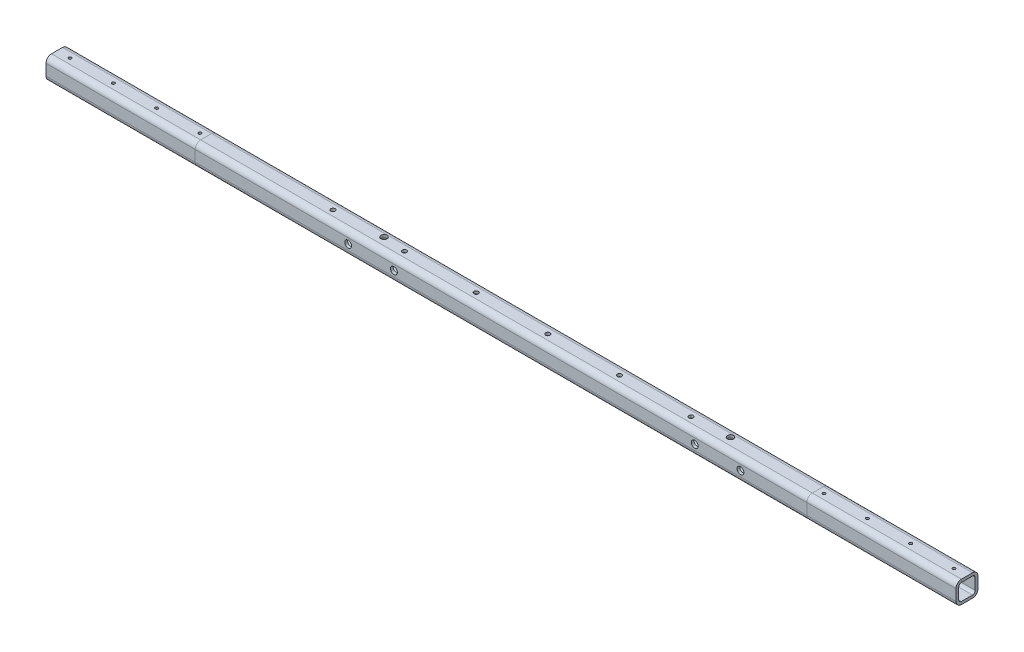
SolidWorks part; units mm, degrees
material "AISI 1015 Acero estirado en frío (SS)"
ref_plane "Alzado" through (0, 0, 0) normal (0, 0, 1) x (1, 0, 0)
ref_plane "Planta" through (0, 0, 0) normal (0, 1, 0) x (1, 0, 0)
ref_plane "Vista lateral" through (0, 0, 0) normal (1, 0, 0) x (0, 0, -1)
sketch "Croquis1" plane through (0, 0, 0) normal (0, 0, 1) x (1, 0, 0)
  line L0 (-623.6352, 0) -> (788.3648, 0)
  dimension "D1" = 1412
other "Miembro estructural1"
ref_plane "Plano1" through (-623.6352, 0, 0) normal (1, 0, 0) x (0, 1, 0)
sketch "Sketch1" plane through (-623.6352, 0, 0) normal (1, 0, 0) x (0, 1, 0)
  line L0 (-12.7, -19.05) -> (12.7, -19.05)
  line L1 (-19.05, -12.7) -> (-19.05, 12.7)
  line L2 (12.7, 19.05) -> (-12.7, 19.05)
  line L3 (19.05, 12.7) -> (19.05, -12.7)
  line L4 (-12.7, -25.4) -> (12.7, -25.4)
  line L5 (-25.4, -12.7) -> (-25.4, 12.7)
  line L6 (12.7, 25.4) -> (-12.7, 25.4)
  line L7 (25.4, 12.7) -> (25.4, -12.7)
  line L8 (0, 0) -> (19.05, 0) construction
  line L9 (0, 0) -> (0, 19.05) construction
  arc A0 (25.4, 12.7) -> (12.7, 25.4) centre (12.7, 12.7) ccw
  arc A1 (12.7, -25.4) -> (25.4, -12.7) centre (12.7, -12.7) ccw
  arc A2 (-25.4, -12.7) -> (-12.7, -25.4) centre (-12.7, -12.7) ccw
  arc A3 (-12.7, 25.4) -> (-25.4, 12.7) centre (-12.7, 12.7) ccw
  arc A4 (-12.7, 19.05) -> (-19.05, 12.7) centre (-12.7, 12.7) ccw
  arc A5 (19.05, 12.7) -> (12.7, 19.05) centre (12.7, 12.7) ccw
  arc A6 (12.7, -19.05) -> (19.05, -12.7) centre (12.7, -12.7) ccw
  arc A7 (-19.05, -12.7) -> (-12.7, -19.05) centre (-12.7, -12.7) ccw
  point P3 (0, 25.4)
  point P4 (25.4, 0)
  point P5 (0, -25.4)
  point P6 (-25.4, 0)
  point P7 (-25.4, 25.4)
  point P8 (-25.4, -25.4)
  point P33 (0, 0)
  point P35 (25.4, -25.4)
  point P36 (25.4, 25.4)
  point P37 (0, 0)
  dimension "D1" = 12.7
  dimension "Thickness" = 6.35
  dimension "V_leg" = 50.8
hole_wizard "Taladro de margen para M61" positions "Croquis4" profile "Croquis5" hole size "M6" standard "Ansi Metric"
sketch "Croquis4" plane through (0, -25.4, 0) normal (0, -1, 0) x (-1, 0, 0)
  line L1 (-82.3648, -25.4) -> (-82.3648, 25.4) construction
  line L2 (-788.3648, -25.4) -> (623.6352, -25.4) construction
  line L3 (-788.3648, 25.4) -> (623.6352, 25.4) construction
  line L7 (-82.3648, 0) -> (-211.5892, 0) construction
  point P0 (-152.3648, 0)
  point P2 (-212.3648, 0)
  dimension "D1" = 70
  dimension "D2" = 130
sketch "Croquis5" plane through (152.3648, -25.4, 0) normal (1, 0, 0) x (0, 0, -1)
  line L0 (0, 0) -> (0, 6.35)
  line L1 (0, 6.35) -> (3.3, 6.35)
  line L2 (3.3, 6.35) -> (3.3, 0)
  line L5 (3.3, 0) -> (0, 0)
  line L11 (0, -6.35) -> (0, 107.95) construction
  dimension "Diámetro de taladro hasta el siguiente" = 6.6
  dimension "Profundidad de taladro hasta el siguiente" = 6.35
ref_plane "Plano2" through (0, 0, 0) normal (0, 0, 1) x (1, 0, 0)
hole_wizard "Taladro de margen para 3/81" positions "Croquis7" profile "Croquis6" hole size "3/8" standard "Ansi Inch"
sketch "Croquis7" plane through (0, 25.4, 0) normal (0, 1, 0) x (1, 0, 0)
  line L1 (-0.3202, 0) -> (165.0498, 0) construction
  line L3 (82.3648, 12.7) -> (82.3648, 0) construction
  line L4 (788.3648, 12.7) -> (-623.6352, 12.7) construction
  point P0 (-331.0602, 0)
  point P2 (-165.6902, 0)
  point P4 (-0.3202, 0)
  point P6 (165.0498, 0)
  point P8 (330.4198, 0)
  point P10 (495.7898, 0)
  dimension "D1" = 165.37
  dimension "D2" = 165.37
  dimension "D3" = 165.37
  dimension "D4" = 165.37
  dimension "D5" = 165.37
sketch "Croquis6" plane through (-331.0602, 25.4, 0) normal (1, 0, 0) x (0, 0, 1)
  line L0 (0, 0) -> (0, 6.35)
  line L1 (0, 6.35) -> (5.0419, 6.35)
  line L2 (5.0419, 6.35) -> (5.0419, 0)
  line L5 (5.0419, 0) -> (0, 0)
  line L11 (0, -6.35) -> (0, 107.95) construction
  dimension "Diámetro de taladro hasta el siguiente" = 10.0838
  dimension "Profundidad de taladro hasta el siguiente" = 6.35
sketch "Croquis8" plane through (0, 0, 0) normal (0, 0, 1) x (1, 0, 0)
  line L0 (-623.6352, 0) -> (-968.0352, 0)
  line L1 (-623.6352, 12.7) -> (-623.6352, -12.7) construction
  line L2 (788.3648, 0) -> (1132.7648, 0)
  line L3 (788.3648, 12.7) -> (788.3648, -12.7) construction
  dimension "D1" = 344.4
  dimension "D2" = 344.4
other "Miembro estructural2"
ref_plane "Plano3" through (-623.6352, 0, 0) normal (-1, 0, 0) x (0, -1, 0)
sketch "Sketch11" plane through (-623.6352, 0, 0) normal (-1, 0, 0) x (0, -1, 0)
  line L0 (-12.7, -19.05) -> (12.7, -19.05)
  line L1 (-19.05, -12.7) -> (-19.05, 12.7)
  line L2 (12.7, 19.05) -> (-12.7, 19.05)
  line L3 (19.05, 12.7) -> (19.05, -12.7)
  line L4 (-12.7, -25.4) -> (12.7, -25.4)
  line L5 (-25.4, -12.7) -> (-25.4, 12.7)
  line L6 (12.7, 25.4) -> (-12.7, 25.4)
  line L7 (25.4, 12.7) -> (25.4, -12.7)
  line L8 (0, 0) -> (19.05, 0) construction
  line L9 (0, 0) -> (0, 19.05) construction
  arc A0 (25.4, 12.7) -> (12.7, 25.4) centre (12.7, 12.7) ccw
  arc A1 (12.7, -25.4) -> (25.4, -12.7) centre (12.7, -12.7) ccw
  arc A2 (-25.4, -12.7) -> (-12.7, -25.4) centre (-12.7, -12.7) ccw
  arc A3 (-12.7, 25.4) -> (-25.4, 12.7) centre (-12.7, 12.7) ccw
  arc A4 (-12.7, 19.05) -> (-19.05, 12.7) centre (-12.7, 12.7) ccw
  arc A5 (19.05, 12.7) -> (12.7, 19.05) centre (12.7, 12.7) ccw
  arc A6 (12.7, -19.05) -> (19.05, -12.7) centre (12.7, -12.7) ccw
  arc A7 (-19.05, -12.7) -> (-12.7, -19.05) centre (-12.7, -12.7) ccw
  point P3 (0, 25.4)
  point P4 (25.4, 0)
  point P5 (0, -25.4)
  point P6 (-25.4, 0)
  point P7 (-25.4, 25.4)
  point P8 (-25.4, -25.4)
  point P33 (0, 0)
  point P35 (25.4, -25.4)
  point P36 (25.4, 25.4)
  point P37 (0, 0)
  dimension "D1" = 12.7
  dimension "Thickness" = 6.35
  dimension "V_leg" = 50.8
hole_wizard "Taladro de margen para 1/41" positions "Croquis10" profile "Croquis9" hole size "1/4" standard "Ansi Inch" end condition up to next
sketch "Croquis10" plane through (0, -25.4, 0) normal (0, -1, 0) x (-1, 0, 0)
  line L0 (-86.538, -12.7) -> (-86.538, 12.7) construction
  line L1 (-788.3648, -12.7) -> (623.6352, -12.7) construction
  line L2 (-788.3648, 12.7) -> (623.6352, 12.7) construction
  line L4 (-86.538, 0) -> (-290.6929, 0) construction
  circle A1 centre (-152.3648, 0) radius 3.3 construction
  circle A2 centre (-212.3648, 0) radius 3.3 construction
  point P0 (-137.3648, 0)
  point P17 (-182.3648, 0)
  point P19 (-227.3648, 0)
  dimension "D1" = 15
  dimension "D2" = 30
  dimension "D3" = 15
sketch "Croquis9" plane through (137.3648, -25.4, 0) normal (1, 0, 0) x (0, 0, -1)
  line L0 (0, 0) -> (0, 6.35)
  line L1 (0, 6.35) -> (3.3782, 6.35)
  line L2 (3.3782, 6.35) -> (3.3782, 0)
  line L5 (3.3782, 0) -> (0, 0)
  line L11 (0, -6.35) -> (0, 107.95) construction
  dimension "Diámetro de taladro hasta el siguiente" = 6.7564
  dimension "Profundidad de taladro hasta el siguiente" = 6.35
hole_wizard "Taladro de margen para 1/42" positions "Croquis12" profile "Croquis11" hole size "1/4" standard "Ansi Inch" end condition up to next
sketch "Croquis12" plane through (0, 25.4, 0) normal (0, 1, 0) x (1, 0, 0)
  line L0 (1132.7648, -12.7) -> (1132.7648, 12.7) construction
  line L1 (82.3648, 12.7) -> (82.3648, -12.7) construction
  line L2 (788.3648, 12.7) -> (-623.6352, 12.7) construction
  line L3 (788.3648, -12.7) -> (-623.6352, -12.7) construction
  point P0 (1102.7648, 0)
  point P15 (1132.7648, 0)
  point P21 (1002.7648, 0)
  point P22 (902.7648, 0)
  point P23 (802.7648, 0)
  point P32 (-638.0352, 0)
  point P33 (-738.0352, 0)
  point P34 (-838.0352, 0)
  point P35 (-938.0352, 0)
  dimension "D1" = 30
  dimension "D3" = 100
  dimension "D2" = 4
sketch "Croquis11" plane through (1102.7648, 25.4, 0) normal (1, 0, 0) x (0, 0, 1)
  line L0 (0, 0) -> (0, 6.351)
  line L1 (0, 6.351) -> (3.3782, 6.351)
  line L2 (3.3782, 6.351) -> (3.3782, 0)
  line L5 (3.3782, 0) -> (0, 0)
  line L11 (0, -6.35) -> (0, 107.95) construction
  dimension "Diámetro de taladro hasta el siguiente" = 6.7564
  dimension "Profundidad de taladro hasta el siguiente" = 6.351
sketch "Sketch12" plane through (0, 0, -25.4) normal (0, 0, -1) x (-1, 0, 0)
  line L16 (-607.3648, -25) -> (-658.1648, -25)
  line L17 (-658.1648, -25) -> (-658.1648, 25)
  line L18 (-658.1648, 25) -> (-607.3648, 25)
  line L19 (-607.3648, 25) -> (-607.3648, -25)
  line L20 (-557.3648, 25) -> (-506.5648, 25)
  line L21 (-506.5648, 25) -> (-506.5648, -25)
  line L22 (-506.5648, -25) -> (-557.3648, -25)
  line L23 (-557.3648, -25) -> (-557.3648, 25)
  line L24 (192.6352, -25) -> (141.8352, -25)
  line L25 (141.8352, -25) -> (141.8352, 25)
  line L26 (141.8352, 25) -> (192.6352, 25)
  line L27 (192.6352, 25) -> (192.6352, -25)
  line L28 (242.6352, 25) -> (293.4352, 25)
  line L29 (293.4352, 25) -> (293.4352, -25)
  line L30 (293.4352, -25) -> (242.6352, -25)
  line L31 (242.6352, -25) -> (242.6352, 25)
  line L32 (623.6352, 12.3) -> (-788.3648, -12.3) construction
  line L33 (-788.3648, 12.3) -> (623.6352, -12.3) construction
  line L40 (-788.3648, 12.3) -> (-788.3648, -12.3)
  line L41 (-788.3648, -12.3) -> (623.6352, -12.3)
  line L42 (623.6352, -12.3) -> (623.6352, 12.3)
  line L43 (623.6352, 12.3) -> (-788.3648, 12.3)
  line L44 (623.6352, -12.3) -> (623.6352, 12.3)
  line L45 (623.6352, 12.3) -> (-788.3648, 12.3) construction
  line L46 (-788.3648, 12.3) -> (-788.3648, -12.3) construction
  line L47 (-788.3648, -12.3) -> (623.6352, -12.3) construction
  circle A1 centre (270.419, 0) radius 7.9375
  circle A3 centre (164.8514, 0) radius 7.9375
  circle A5 centre (-529.581, 0) radius 7.9375
  circle A7 centre (-635.1486, 0) radius 7.9375
extrude "Cut-Extrude1" cut sketch "Sketch12" against normal up to surface (50.8 mm away) contours A1 | A3 | A5 | A7 up to face at (82.3648, 0, 25.4)
sketch "Sketch13" plane through (0, 25.4, 0) normal (0, 1, 0) x (-1, 0, 0)
  line L0 (217.6352, 25.4) -> (217.6352, 0) construction
  line L1 (-176.3648, 12.7) -> (-1588.3648, 12.7) construction
  line L2 (227.9652, 12.7) -> (207.5352, 12.7) construction
  line L3 (-176.3648, -12.7) -> (-176.3648, 12.7)
  line L4 (227.9652, -24.6) -> (227.9652, 25.4)
  line L8 (227.9652, 25.4) -> (207.5352, 25.4)
  line L9 (207.5352, 25.4) -> (207.5352, -24.6)
  line L12 (227.9652, -11.9) -> (207.5352, -11.9) construction
  line L13 (623.6352, -12.7) -> (623.6352, 12.7)
  line L14 (623.6352, 12.7) -> (-788.3648, 12.7)
  line L15 (-788.3648, 12.7) -> (-788.3648, -12.7)
  line L16 (-788.3648, -12.7) -> (623.6352, -12.7)
  line L19 (230.0502, -24.6) -> (205.4502, -24.6)
  line L21 (217.7502, 25.4) -> (217.7502, -24.6) construction
  line L22 (623.6352, -12.7) -> (623.6352, 12.7)
  line L23 (623.6352, 12.7) -> (-788.3648, 12.7) construction
  line L24 (-788.3648, 12.7) -> (-788.3648, -12.7)
  line L25 (-788.3648, -12.7) -> (623.6352, -12.7)
  arc A0 (-575.2498, -4.6) -> (-589.2498, -4.6) centre (-582.2498, -4.6) ccw
  arc A1 (-589.2498, -4.6) -> (-575.2498, -4.6) centre (-582.2498, -4.6) ccw
  arc A113 (210.7502, -4.6) -> (224.7502, -4.6) centre (217.7502, -4.6) ccw
  arc A115 (224.7502, -4.6) -> (210.7502, -4.6) centre (217.7502, -4.6) ccw
  dimension "D2" = 406
  dimension "D1" = 0
  dimension "D3" = 2
extrude "Cut-Extrude2" cut sketch "Sketch13" against normal up to surface (50.8 mm away) contours A115 A113 | A0 A1 up to face at (137.3648, -25.4, -3.3782)
equation "\"d1\"=165.37"
